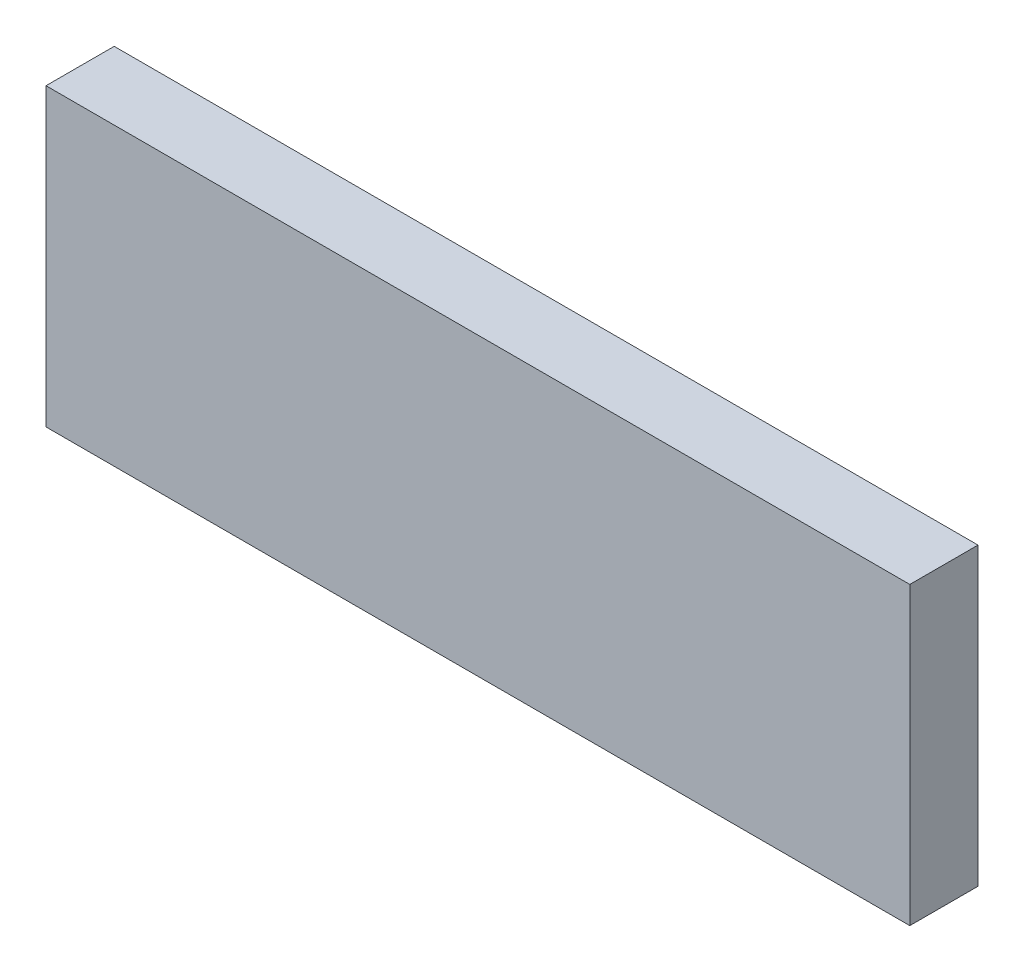
SolidWorks part; units mm, degrees
ref_plane "前视基准面" through (0, 0, 0) normal (0, 0, 1) x (1, 0, 0)
ref_plane "上视基准面" through (0, 0, 0) normal (0, 1, 0) x (1, 0, 0)
ref_plane "右视基准面" through (0, 0, 0) normal (1, 0, 0) x (0, 0, -1)
sketch "草图1" plane through (0, 0, 0) normal (0, 0, 1) x (1, 0, 0)
  line L1 (-63.2282, 32.349) -> (-25.2282, 32.349)
  line L2 (-63.2282, 32.349) -> (-63.2282, 19.349)
  line L3 (-63.2282, 19.349) -> (-25.2282, 19.349)
  line L4 (-25.2282, 32.349) -> (-25.2282, 19.349)
  dimension "D1" = 38
  dimension "D2" = 13
extrude "凸台-拉伸1" add sketch "草图1" along normal blind 3
